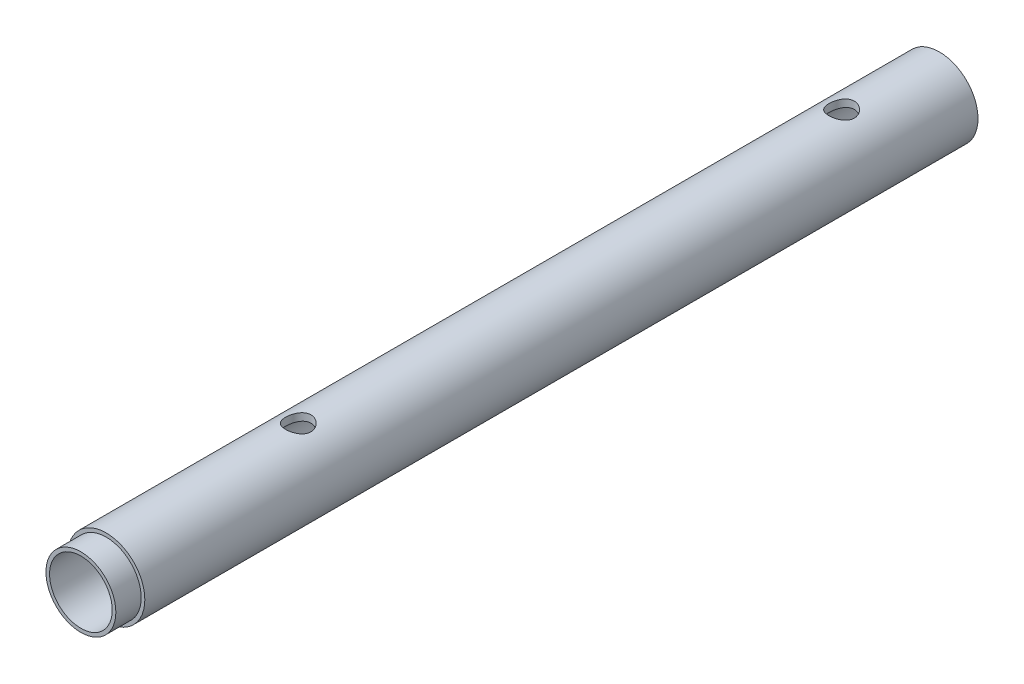
SolidWorks part; units mm, degrees
material "Galvanized Steel"
ref_plane "Front Plane" through (0, 0, 0) normal (0, 0, 1) x (1, 0, 0)
ref_plane "Top Plane" through (0, 0, 0) normal (0, 1, 0) x (1, 0, 0)
ref_plane "Right Plane" through (0, 0, 0) normal (1, 0, 0) x (0, 0, -1)
sketch "Sketch1" plane through (0, 0, 0) normal (0, 0, 1) x (1, 0, 0)
  circle A0 centre (0, 0) radius 10.65
  circle A1 centre (0, 0) radius 8.65
  dimension "D1" = 21.3
  dimension "D2" = 2
extrude "Boss-Extrude1" add sketch "Sketch1" along normal blind 237
sketch "Sketch2" plane through (0, 0, 0) normal (0, 1, 0) x (1, 0, 0)
  line L0 (-10.65, -237) -> (10.65, -237) construction
  circle A0 centre (0, -177) radius 3.5
  dimension "D1" = 7
  dimension "D2" = 60
extrude "Cut-Extrude1" cut sketch "Sketch2" against normal through all both and the other way through all
pattern_linear "LPattern1" count 2 spacing 150 along (0, 0, -1) of "Cut-Extrude1"
sketch "Sketch3" plane through (0, 0, 0) normal (0, 1, 0) x (1, 0, 0)
  line L0 (0, -237) -> (0, -221.8415)
  line L1 (-10.65, -237) -> (-9.65, -237)
  line L2 (-10.65, -237) -> (-10.65, -230)
  line L3 (-10.65, -230) -> (-9.65, -230)
  line L4 (-9.65, -237) -> (-9.65, -230)
  line L5 (-10.65, -237) -> (-9.65, -230) construction
  line L6 (-10.65, -230) -> (-9.65, -237) construction
  line L7 (-10.65, -237) -> (10.65, -237) construction
  point P4 (-10.15, -233.5)
  dimension "D1" = 7
  dimension "D2" = 1
revolve "Cut-Revolve1" cut sketch "Sketch3" angle 360 about L0
